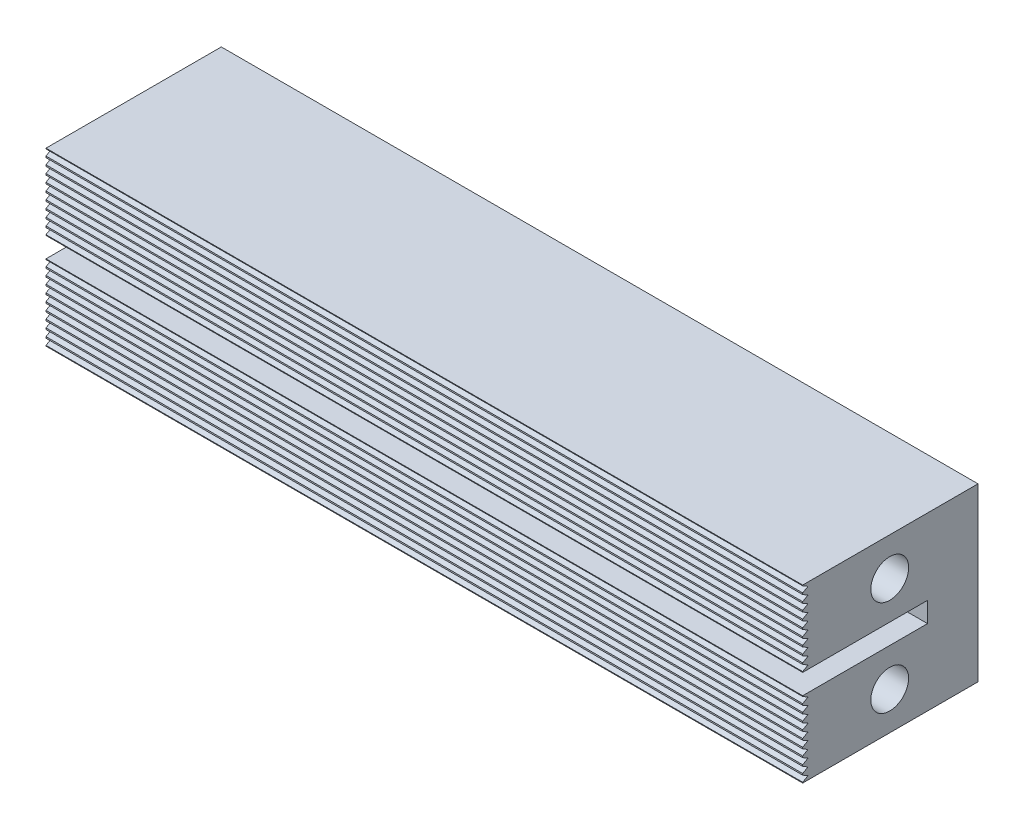
SolidWorks part; units mm, degrees
ref_plane "Front Plane" through (0, 0, 0) normal (0, 0, 1) x (1, 0, 0)
ref_plane "Top Plane" through (0, 0, 0) normal (0, 1, 0) x (1, 0, 0)
ref_plane "Right Plane" through (0, 0, 0) normal (1, 0, 0) x (0, 0, -1)
sketch "Sketch1" plane through (0, 0, 0) normal (0, 0, 1) x (1, 0, 0)
  line L5 (0, 0) -> (150, 0)
  line L6 (0, 0) -> (0, 34)
  line L7 (0, 34) -> (150, 34)
  line L8 (150, 0) -> (150, 34)
  dimension "D1" = 34
  dimension "D2" = 150
extrude "Boss-Extrude1" add sketch "Sketch1" along normal blind 35
sketch "Sketch2" plane through (150, 0, 0) normal (1, 0, 0) x (0, 0, -1)
  line L0 (-35, 17) -> (-35, 19)
  line L1 (-35, 0) -> (-35, 34) construction
  line L2 (-35, 19) -> (-10, 19)
  line L3 (-10, 19) -> (-10, 15)
  line L4 (-10, 15) -> (-35, 15)
  line L5 (-35, 15) -> (-35, 17)
  line L6 (-35, 0) -> (0, 0) construction
  dimension "D1" = 25
  dimension "D2" = 15
  dimension "D3" = 4
extrude "Cut-Extrude1" cut sketch "Sketch2" against normal blind 160
sketch "Sketch3" plane through (150, 0, 0) normal (1, 0, 0) x (0, 0, -1)
  line L1 (-35, 32.5) -> (-33.7, 31.75)
  line L3 (-33.7, 31.75) -> (-35, 31)
  line L8 (-35, 19) -> (-35, 34) construction
  line L9 (-35, 34) -> (-33.7, 34.75)
  line L10 (-35, 34) -> (-31.5992, 34) construction
  line L11 (-35, 34) -> (-33.7, 33.25)
  line L12 (-35, 34) -> (-35, 32.5)
  line L13 (-33.7, 33.25) -> (-35, 32.5)
  line L14 (-33.7, 34.75) -> (-35, 34.75)
  line L15 (-35, 34.75) -> (-35, 34)
  line L16 (-35, 32.5) -> (-35, 31)
  line L17 (-35, 31) -> (-33.7, 30.25)
  line L18 (-33.7, 30.25) -> (-35, 29.5)
  line L19 (-35, 31) -> (-35, 29.5)
  line L20 (-35, 29.5) -> (-33.7, 28.75)
  line L21 (-33.7, 28.75) -> (-35, 28)
  line L22 (-35, 29.5) -> (-35, 28)
  line L23 (-35, 28) -> (-33.7, 27.25)
  line L24 (-33.7, 27.25) -> (-35, 26.5)
  line L25 (-35, 28) -> (-35, 26.5)
  line L26 (-35, 26.5) -> (-33.7, 25.75)
  line L27 (-33.7, 25.75) -> (-35, 25)
  line L28 (-35, 26.5) -> (-35, 25)
  line L29 (-35, 25) -> (-33.7, 24.25)
  line L30 (-33.7, 24.25) -> (-35, 23.5)
  line L31 (-35, 25) -> (-35, 23.5)
  line L32 (-35, 23.5) -> (-33.7, 22.75)
  line L33 (-33.7, 22.75) -> (-35, 22)
  line L34 (-35, 23.5) -> (-35, 22)
  line L35 (-35, 22) -> (-33.7, 21.25)
  line L36 (-33.7, 21.25) -> (-35, 20.5)
  line L37 (-35, 22) -> (-35, 20.5)
  line L38 (-35, 20.5) -> (-33.7, 19.75)
  line L39 (-33.7, 19.75) -> (-35, 19)
  line L40 (-35, 20.5) -> (-35, 19)
  dimension "D1" = 119.982
  dimension "D2" = 1.5
  dimension "D3" = 1.3
  dimension "D4" = 0.75
  dimension "D6" = 1.5
  dimension "D5" = 10
ref_plane "Plane2" through (0, 17, 0) normal (0, 1, 0) x (1, 0, 0)
sketch "Sketch7" plane through (150, 0, 0) normal (1, 0, 0) x (0, 0, -1)
  line L0 (-17.5, 34) -> (-17.5, 26.5) construction
  line L2 (-35, 34) -> (0, 34) construction
  line L3 (18.535, 17) -> (-18.535, 17) construction
  circle A0 centre (-17.5, 26.5) radius 3.75
  circle A1 centre (-17.5, 7.5) radius 3.75
  dimension "D1" = 7.5
  dimension "D2" = 7.5
extrude "Cut-Extrude9" cut sketch "Sketch7" against normal blind 160
extrude "Cut-Extrude11" cut sketch "Sketch3" against normal through all contours L39 L38 L28 | L36 L35 L28 | L33 L32 L28 | L30 L29 L28 | L27 L26 L28 | L24 L23 L28 | L21 L20 L28 | L18 L17 L28 | L3 L1 L28 | L13 L11 L28
mirror "Mirror1" about plane through (0, 17, 0) normal (0, 1, 0) of "Cut-Extrude11"
sketch "Sketch8" plane through (150, 0, 0) normal (1, 0, 0) x (0, 0, -1)
  line L1 (-35, 34) -> (-34.75, 34)
  line L2 (-35, 34) -> (-35, 0)
  line L3 (-35, 0) -> (-34.75, 0)
  line L4 (-34.75, 34) -> (-34.75, 0)
extrude "Cut-Extrude12" cut sketch "Sketch8" against normal through all contours L2 L1 L4 L3
sketch "Sketch9" plane through (0, 0, 0) normal (0, 0, -1) x (-1, 0, 0)
  line L0 (-75, 47.004) -> (-75, -17.2067) construction
  line L1 (-153.0519, 17) -> (4.0503, 17) construction
  line L2 (0, 0) -> (-150, 0) construction
  line L3 (0, 34) -> (0, 0) construction
  line L4 (-150, 34) -> (0, 34) construction
  circle A1 centre (-50, 17) radius 4
  circle A2 centre (-100, 17) radius 4
  dimension "D1" = 25
  dimension "D3" = 8
  dimension "D4" = 17
  dimension "D6" = 50
  dimension "D7" = 8
  dimension "D2" = 25
  dimension "D5" = 100
  dimension "D8" = 157.1022
  dimension "D9" = 17
extrude "Cut-Extrude13" cut sketch "Sketch9" against normal blind 5
